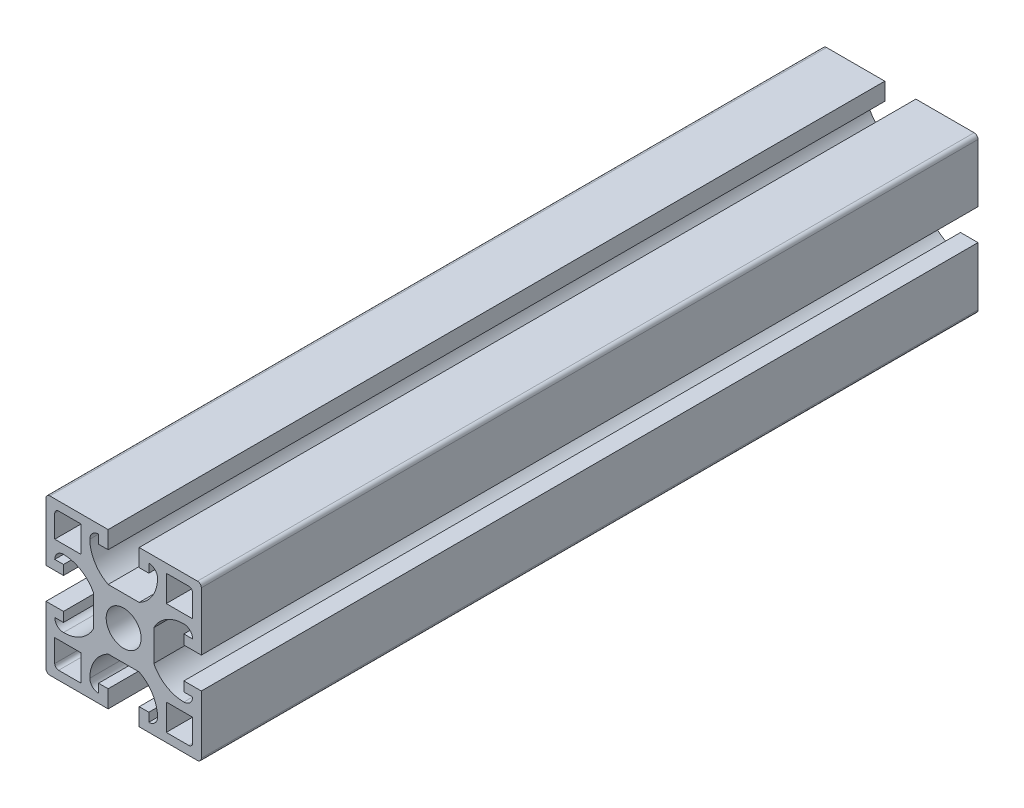
SolidWorks part; units mm, degrees
material "3.0255 (EN-AW 1350A)"
ref_plane "Płaszczyzna przednia" through (0, 0, 0) normal (0, 0, 1) x (1, 0, 0)
ref_plane "Płaszczyzna górna" through (0, 0, 0) normal (0, 1, 0) x (1, 0, 0)
ref_plane "Płaszczyzna prawa" through (0, 0, 0) normal (1, 0, 0) x (0, 0, -1)
sketch "Szkic1" plane through (0, 0, 0) normal (0, 0, 1) x (1, 0, 0)
  line L0 (4, 7.7548) -> (-4, 7.7548)
  line L1 (7.75, 4) -> (7.75, -4)
  line L13 (0, 20) -> (0, 0) construction
  line L15 (4, 20) -> (4, 15.5)
  line L16 (4, 15.5) -> (6.4671, 15.5)
  line L27 (6.4671, 15.5) -> (6.4671, 17.75)
  line L35 (-9.3131, 0) -> (57.7694, 0) construction
  line L53 (-10.9671, 17.7542) -> (-17.75, 10.9714) construction
  line L54 (15.5, 6.4714) -> (17.75, 6.4714)
  line L55 (15.5, 4) -> (15.5, 6.4714)
  line L56 (20, 4) -> (15.5, 4)
  line L70 (20, 19) -> (20, 4)
  line L76 (4, 20) -> (19, 20)
  line L82 (-10.9671, 10.9714) -> (-17.75, 17.7542) construction
  line L83 (-17.75, 10.9714) -> (-17.75, 16.7542)
  line L88 (-10.9671, 17.7542) -> (-16.75, 17.7542)
  line L89 (-10.9671, 10.9714) -> (-10.9671, 17.7542)
  line L91 (-10.9671, 10.9714) -> (-17.75, 10.9714)
  line L92 (-4, 20) -> (-19, 20)
  line L96 (-20, 19) -> (-20, 4)
  line L99 (10.9671, 10.9714) -> (17.75, 10.9714)
  line L100 (10.9671, 10.9714) -> (10.9671, 17.7542)
  line L101 (10.9671, 17.7542) -> (16.75, 17.7542)
  line L102 (17.75, 10.9714) -> (17.75, 16.7542)
  line L103 (10.9671, 10.9714) -> (17.75, 17.7542) construction
  line L104 (10.9671, 17.7542) -> (17.75, 10.9714) construction
  line L105 (-20, 4) -> (-15.5, 4)
  line L106 (-15.5, 4) -> (-15.5, 6.4714)
  line L107 (-15.5, 6.4714) -> (-17.75, 6.4714)
  line L108 (-6.4671, 15.5) -> (-6.4671, 17.75)
  line L109 (-4, 15.5) -> (-6.4671, 15.5)
  line L110 (-4, 20) -> (-4, 15.5)
  line L111 (-7.75, 4) -> (-7.75, -4)
  line L113 (10.9671, -17.7542) -> (17.75, -10.9714) construction
  line L114 (10.9671, -10.9714) -> (17.75, -17.7542) construction
  line L115 (-10.9671, -10.9714) -> (-17.75, -17.7542) construction
  line L116 (-10.9671, -17.7542) -> (-17.75, -10.9714) construction
  line L117 (-4, -20) -> (-4, -15.5)
  line L118 (-4, -15.5) -> (-6.4671, -15.5)
  line L119 (-6.4671, -15.5) -> (-6.4671, -17.75)
  line L120 (-15.5, -6.4714) -> (-17.75, -6.4714)
  line L121 (-15.5, -4) -> (-15.5, -6.4714)
  line L122 (-20, -4) -> (-15.5, -4)
  line L123 (17.75, -10.9714) -> (17.75, -16.7542)
  line L124 (10.9671, -17.7542) -> (16.75, -17.7542)
  line L125 (10.9671, -10.9714) -> (10.9671, -17.7542)
  line L126 (10.9671, -10.9714) -> (17.75, -10.9714)
  line L127 (-20, -19) -> (-20, -4)
  line L128 (-4, -20) -> (-19, -20)
  line L129 (-10.9671, -10.9714) -> (-17.75, -10.9714)
  line L130 (-10.9671, -10.9714) -> (-10.9671, -17.7542)
  line L131 (-10.9671, -17.7542) -> (-16.75, -17.7542)
  line L132 (-17.75, -10.9714) -> (-17.75, -16.7542)
  line L133 (4, -20) -> (19, -20)
  line L134 (20, -19) -> (20, -4)
  line L135 (20, -4) -> (15.5, -4)
  line L136 (15.5, -4) -> (15.5, -6.4714)
  line L137 (15.5, -6.4714) -> (17.75, -6.4714)
  line L138 (6.4671, -15.5) -> (6.4671, -17.75)
  line L139 (4, -15.5) -> (6.4671, -15.5)
  line L140 (4, -20) -> (4, -15.5)
  line L141 (4, -7.7548) -> (-4, -7.7548)
  arc A2 (6.4671, 17.75) -> (8.7171, 15.5) centre (6.4671, 15.5) cw
  arc A3 (8.7171, 15.5) -> (4, 7.7548) centre (0, 15.5) cw
  arc A18 (15.5, 8.7214) -> (7.75, 4) centre (15.5, 0) ccw
  arc A19 (17.75, 6.4714) -> (15.5, 8.7214) centre (15.5, 6.4714) ccw
  arc A41 (19, 20) -> (20, 19) centre (19, 19) cw
  arc A42 (16.75, 17.7542) -> (17.75, 16.7542) centre (16.75, 16.7542) cw
  arc A43 (-16.75, 17.7542) -> (-17.75, 16.7542) centre (-16.75, 16.7542) ccw
  arc A44 (-19, 20) -> (-20, 19) centre (-19, 19) ccw
  arc A45 (-17.75, 6.4714) -> (-15.5, 8.7214) centre (-15.5, 6.4714) cw
  arc A46 (-15.5, 8.7214) -> (-7.75, 4) centre (-15.5, 0) cw
  arc A47 (-8.7171, 15.5) -> (-4, 7.7548) centre (0, 15.5) ccw
  arc A48 (-6.4671, 17.75) -> (-8.7171, 15.5) centre (-6.4671, 15.5) ccw
  arc A49 (-6.4671, -17.75) -> (-8.7171, -15.5) centre (-6.4671, -15.5) cw
  arc A50 (-8.7171, -15.5) -> (-4, -7.7548) centre (0, -15.5) cw
  arc A51 (-15.5, -8.7214) -> (-7.75, -4) centre (-15.5, 0) ccw
  arc A52 (-17.75, -6.4714) -> (-15.5, -8.7214) centre (-15.5, -6.4714) ccw
  arc A53 (-19, -20) -> (-20, -19) centre (-19, -19) cw
  arc A54 (-16.75, -17.7542) -> (-17.75, -16.7542) centre (-16.75, -16.7542) cw
  arc A55 (16.75, -17.7542) -> (17.75, -16.7542) centre (16.75, -16.7542) ccw
  arc A56 (19, -20) -> (20, -19) centre (19, -19) ccw
  arc A57 (17.75, -6.4714) -> (15.5, -8.7214) centre (15.5, -6.4714) cw
  arc A58 (15.5, -8.7214) -> (7.75, -4) centre (15.5, 0) cw
  arc A59 (8.7171, -15.5) -> (4, -7.7548) centre (0, -15.5) ccw
  arc A60 (6.4671, -17.75) -> (8.7171, -15.5) centre (6.4671, -15.5) ccw
  circle A61 centre (0, 0) radius 4.5
  point P1 (-14.3586, 14.3628)
  point P2 (14.3586, -14.3628)
  point P47 (0, 7.7548)
  point P92 (-7.75, 0)
  point P100 (7.75, 0)
  point P101 (0, -7.7548)
  point P102 (-14.3586, -14.3628)
  point P162 (14.3586, 14.3628)
  dimension "D4" = 15
  dimension "D5" = 15
  dimension "D9" = 7.75
  dimension "D11" = 7.7548
  dimension "D12" = 4.7214
  dimension "D16" = 1
  dimension "D3" = 4.5
  dimension "D2" = 2.25
  dimension "D10" = 2.2458
  dimension "D18" = 9
  dimension "D6" = 4
  dimension "D7" = 4
  dimension "D8" = 4.5
  dimension "D13" = 2.25
  dimension "D14" = 2.25
  dimension "D15" = 2.25
  dimension "D17" = 2.4671
extrude "Dodanie-wyciągnięcie1" add sketch "Szkic1" along normal blind 200
